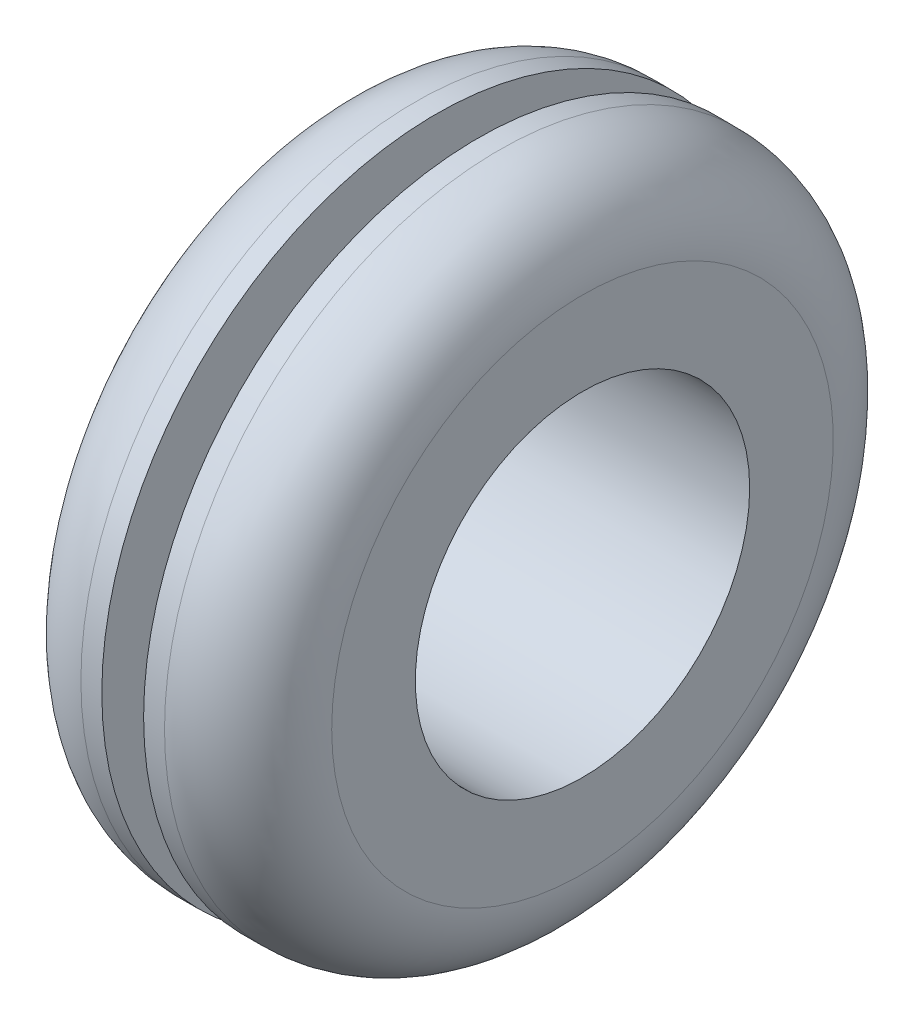
SolidWorks part; units mm, degrees
ref_plane "Спереди" through (0, 0, 0) normal (0, 0, 1) x (1, 0, 0)
ref_plane "Сверху" through (0, 0, 0) normal (0, 1, 0) x (1, 0, 0)
ref_plane "Справа" through (0, 0, 0) normal (1, 0, 0) x (0, 0, -1)
sketch "Эскиз1" plane through (0, 0, 0) normal (0, 0, 1) x (1, 0, 0)
  line L1 (-26.283, 8) -> (-26.283, 0)
  line L2 (-26.283, 8) -> (-23.783, 8)
  line L3 (-23.783, 8) -> (-23.783, 6)
  line L4 (-23.783, 6) -> (-22.783, 6)
  line L5 (-22.783, 8) -> (-22.783, 6)
  line L6 (-22.783, 8) -> (-20.283, 8)
  line L7 (-20.283, 8) -> (-20.283, 0)
  line L8 (-26.283, 0) -> (-20.283, 0)
  line L10 (-31.1145, 0) -> (-14.0531, 0) construction
  dimension "D1" = 8
  dimension "D2" = 1
  dimension "D3" = 6
  dimension "D4" = 6
  dimension "D5" = 8
  dimension "D6" = 2.5
revolve "Повернуть1" add sketch "Эскиз1" angle 360 about L10
sketch "Эскиз2" plane through (-20.283, 0, 0) normal (1, 0, 0) x (0, 0, -1)
  circle A0 centre (0, 0) radius 4
  dimension "D1" = 8
extrude "Вырез-Вытянуть1" cut sketch "Эскиз2" against normal blind 10
fillet "Скругление1" radius 2 2 edges at (-26.283, 0, 8) (-20.283, 0, 8)
